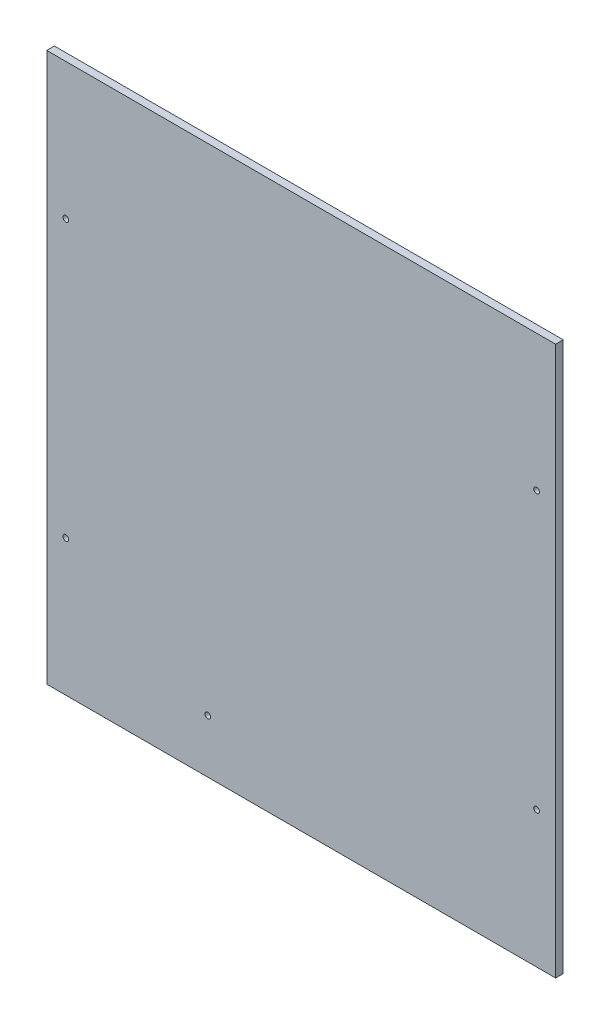
SolidWorks part; units mm, degrees
ref_plane "Plan de face" through (0, 0, 0) normal (0, 0, 1) x (1, 0, 0)
ref_plane "Plan de dessus" through (0, 0, 0) normal (0, 1, 0) x (1, 0, 0)
ref_plane "Plan de droite" through (0, 0, 0) normal (1, 0, 0) x (0, 0, -1)
sketch "Esquisse1" plane through (0, 0, 0) normal (0, 0, 1) x (1, 0, 0)
  line L0 (0, 182.1442) -> (0, 37.1442) construction
  line L1 (-10, 253.6442) -> (257, 253.6442)
  line L2 (-10, 253.6442) -> (-10, -34.3558)
  line L3 (-10, -34.3558) -> (257, -34.3558)
  line L4 (257, 253.6442) -> (257, -34.3558)
  line L5 (247, 182.1442) -> (247, 37.1442) construction
  circle A0 centre (0, 182.1442) radius 1.5
  circle A1 centre (0, 37.1442) radius 1.5
  circle A2 centre (247, 37.1442) radius 1.5
  circle A3 centre (247, 182.1442) radius 1.5
  circle A4 centre (74.5, -6.3558) radius 1.5
  dimension "D9" = 28
  dimension "D1" = 288
  dimension "D2" = 267
  dimension "D3" = 71.5
  dimension "D4" = 71.5
  dimension "D5" = 71.5
  dimension "D6" = 71.5
  dimension "D7" = 10
  dimension "D8" = 10
  dimension "D10" = 84.5
extrude "Extrusion1" add sketch "Esquisse1" along normal blind 4
